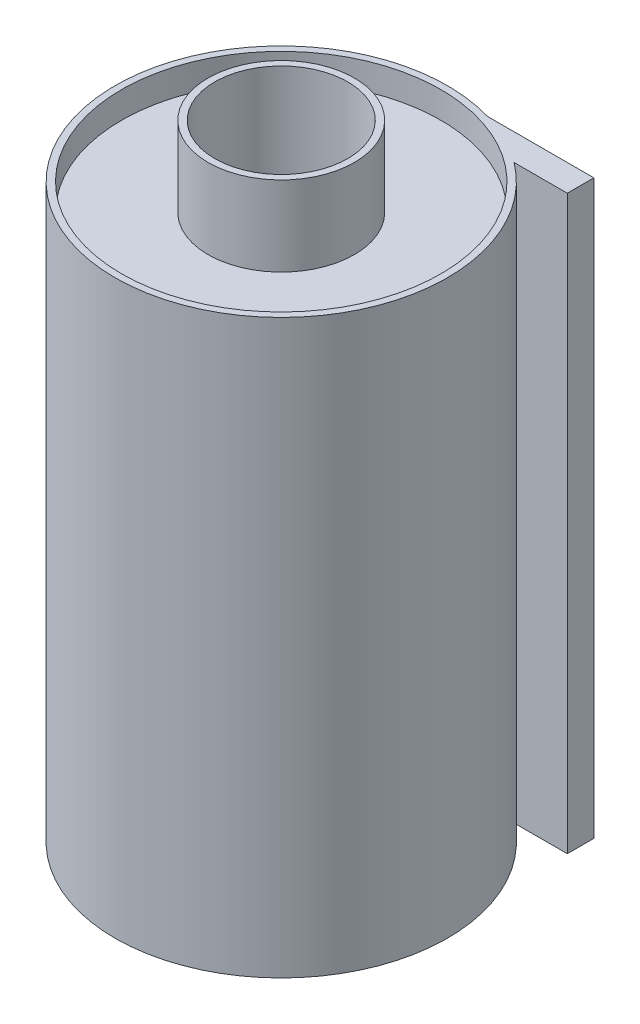
SolidWorks part; units mm, degrees
material "1060 Alloy"
ref_plane "Front Plane" through (0, 0, 0) normal (0, 0, 1) x (1, 0, 0)
ref_plane "Top Plane" through (0, 0, 0) normal (0, 1, 0) x (1, 0, 0)
ref_plane "Right Plane" through (0, 0, 0) normal (1, 0, 0) x (0, 0, -1)
sketch "Sketch1" plane through (0, 0, 0) normal (0, 1, 0) x (1, 0, 0)
  circle A0 centre (0, 0) radius 12.5
  dimension "D1" = 25
extrude "Enclosure" add sketch "Sketch1" along normal blind 41
sketch "Sketch3" plane through (0, 41, 0) normal (0, 1, 0) x (1, 0, 0)
  circle A0 centre (0, 0) radius 12.5
  circle A2 centre (0, 0) radius 12.5 construction
  circle A3 centre (0, 0) radius 12
  dimension "D1" = 0.5
extrude "Upper Lip" add sketch "Sketch3" along normal blind 2
sketch "Sketch4" plane through (0, 41, 0) normal (0, 1, 0) x (1, 0, 0)
  circle A0 centre (0, 0) radius 5.5
  dimension "D1" = 11
extrude "Upper Shaft" add sketch "Sketch4" along normal blind 6
sketch "Sketch5" plane through (0, 47, 0) normal (0, 1, 0) x (1, 0, 0)
  circle A0 centre (0, 0) radius 5
  circle A1 centre (0, 0) radius 5.5 construction
  dimension "D1" = 0.5
extrude "Central Cut" cut sketch "Sketch5" against normal through all
sketch "Sketch6" plane through (0, 0, 0) normal (0, -1, 0) x (1, 0, 0)
  circle A0 centre (0, 0) radius 12
  circle A1 centre (0, 0) radius 12.5 construction
  dimension "D1" = 0.5
extrude "Lower Lip" cut sketch "Sketch6" against normal blind 2
sketch "Sketch7" plane through (0, 2, 0) normal (0, -1, 0) x (-1, 0, 0)
  circle A0 centre (0, 0) radius 5.5
  circle A1 centre (0, 0) radius 5 construction
  circle A2 centre (0, 0) radius 5
  dimension "D1" = 0.5
extrude "Lower Shaft" add sketch "Sketch7" along normal blind 1
sketch "Sketch8" plane through (0, 43, 0) normal (0, 1, 0) x (1, 0, 0)
  line L0 (3.5, 12) -> (11.5, 12)
  line L1 (11.5, 12) -> (11.5, 10)
  line L2 (11.5, 10) -> (7.5, 10)
  circle A0 centre (0, 0) radius 12.5 construction
  circle A1 centre (0, 0) radius 5 construction
  arc A2 (7.5, 10) -> (3.5, 12) centre (0, 0) ccw
  dimension "D1" = 10
  dimension "D2" = 2
  dimension "D3" = 4
extrude "Film Lip" add sketch "Sketch8" against normal up to surface (43 mm away) up to face at (0, 0, -12)
